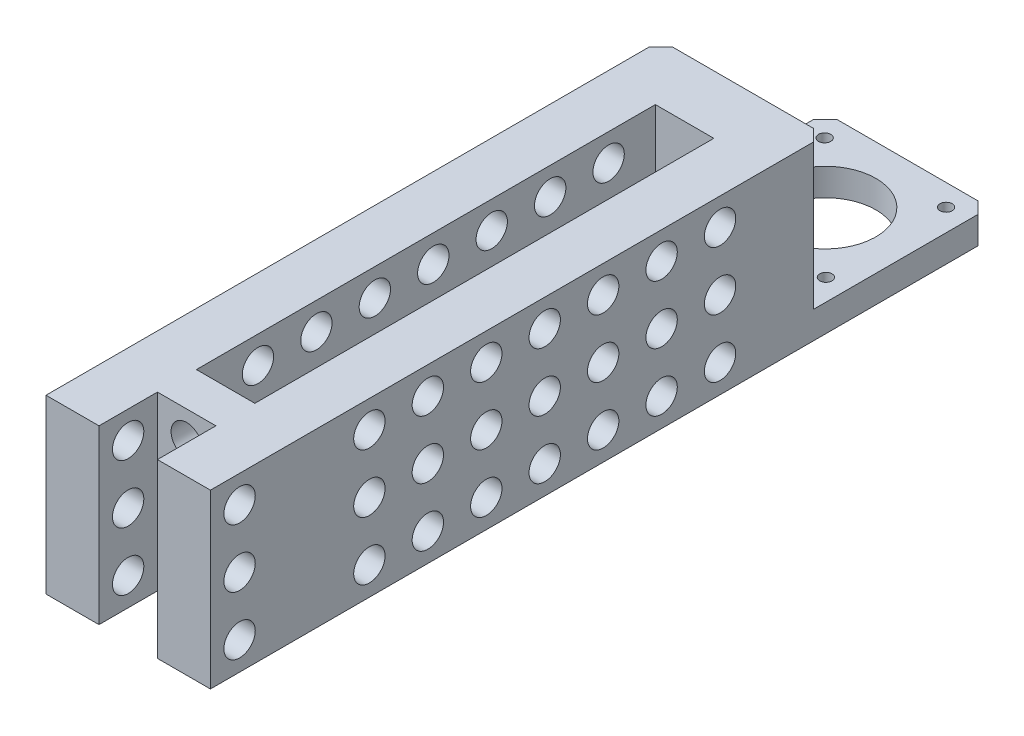
SolidWorks part; units mm, degrees
ref_plane "Front Plane" through (0, 0, 0) normal (0, 0, 1) x (1, 0, 0)
ref_plane "Top Plane" through (0, 0, 0) normal (0, 1, 0) x (1, 0, 0)
ref_plane "Right Plane" through (0, 0, 0) normal (1, 0, 0) x (0, 0, -1)
sketch "Sketch1" plane through (0, 0, 0) normal (0, 1, 0) x (1, 0, 0)
  line L0 (0, 0) -> (-42.2, 0)
  line L1 (-42.2, 0) -> (-42.2, -200)
  line L2 (-42.2, -200) -> (-28.6, -200)
  line L3 (-28.6, -200) -> (-28.6, -185)
  line L4 (-28.6, -185) -> (-13.6, -185)
  line L5 (-13.6, -185) -> (-13.6, -200)
  line L6 (-13.6, -200) -> (0, -200)
  line L7 (0, -200) -> (0, 0)
  line L8 (-28.6, -175) -> (-13.6, -175)
  line L9 (-13.6, -175) -> (-13.6, -57.2)
  line L10 (-13.6, -57.2) -> (-28.6, -57.2)
  line L11 (-28.6, -57.2) -> (-28.6, -175)
  dimension "D1" = 42.2
  dimension "D2" = 57.2
  dimension "D3" = 200
  dimension "D4" = 15
  dimension "D5" = 10
  dimension "D6" = 15
extrude "Boss-Extrude1" add sketch "Sketch1" along normal blind 44.2
sketch "Sketch2" plane through (0, 44.2, 0) normal (0, 1, 0) x (1, 0, 0)
  line L0 (-42.2, 0) -> (0, 0)
  line L1 (0, 0) -> (0, -42.2)
  line L2 (0, -200) -> (0, 0) construction
  line L3 (0, -42.2) -> (-42.2, -42.2)
  line L4 (-42.2, 0) -> (-42.2, -200) construction
  line L5 (-42.2, -42.2) -> (-42.2, 0)
  dimension "D1" = 42.2
extrude "Cut-Extrude1" cut sketch "Sketch2" against normal blind 37.2
sketch "Sketch3" plane through (0, 0, 0) normal (0, -1, 0) x (1, 0, 0)
  line L2 (0, 0) -> (-42.2, 0) construction
  line L3 (-42.2, 0) -> (-42.2, 200) construction
  line L4 (-36.6807, 5.6807) -> (-5.5193, 36.5193) construction
  circle A0 centre (-21.1, 21.1) radius 13
  circle A1 centre (-36.5193, 36.6807) radius 1.575
  circle A2 centre (-5.5193, 36.5193) radius 1.575
  circle A3 centre (-5.6807, 5.5193) radius 1.575
  circle A4 centre (-36.6807, 5.6807) radius 1.575
  circle A5 centre (-21.1, 50) radius 4.1
  circle A6 centre (-5.6, 50) radius 4.1
  circle A7 centre (-36.6, 50) radius 4.1
  point P13 (-21.1, 21.1)
  dimension "D5" = 26
  dimension "D6" = 3.15
  dimension "D8" = 8.2
  dimension "D2" = 21.1
  dimension "D3" = 21.1
  dimension "D4" = 31
  dimension "D7" = 50
  dimension "D9" = 21.1
  dimension "D10" = 2
  dimension "D11" = 2
  dimension "D1" = 4
extrude "Cut-Extrude2" cut sketch "Sketch3" against normal blind 30
sketch "Sketch5" plane through (0, 0, 0) normal (1, 0, 0) x (0, 0, -1)
  line L0 (-200, 44.2) -> (-42.2, 44.2) construction
  line L1 (-42.2, 7) -> (-42.2, 44.2) construction
  line L2 (-200, 44.2) -> (-200, 0) construction
  circle A0 centre (-69.2, 37.2) radius 4.025
  circle A1 centre (-84.2, 37.2) radius 4.025
  circle A2 centre (-99.2, 37.2) radius 4.025
  circle A3 centre (-114.2, 37.2) radius 4.025
  circle A4 centre (-84.2, 22.2) radius 4.025
  circle A5 centre (-99.2, 22.2) radius 4.025
  circle A6 centre (-114.2, 22.2) radius 4.025
  circle A7 centre (-84.2, 7.2) radius 4.025
  circle A8 centre (-99.2, 7.2) radius 4.025
  circle A9 centre (-114.2, 7.2) radius 4.025
  circle A10 centre (-69.2, 22.2) radius 4.025
  circle A11 centre (-69.2, 7.2) radius 4.025
  circle A12 centre (-192.52, 37.2) radius 4.025
  circle A13 centre (-192.52, 22.2) radius 4.025
  circle A14 centre (-192.52, 7.2) radius 4.025
  circle A15 centre (-129.2, 37.2) radius 4.025
  circle A16 centre (-144.2, 37.2) radius 4.025
  circle A17 centre (-159.2, 37.2) radius 4.025
  circle A19 centre (-129.2, 22.2) radius 4.025
  circle A20 centre (-144.2, 22.2) radius 4.025
  circle A21 centre (-159.2, 22.2) radius 4.025
  circle A23 centre (-129.2, 7.2) radius 4.025
  circle A24 centre (-144.2, 7.2) radius 4.025
  circle A25 centre (-159.2, 7.2) radius 4.025
  dimension "D1" = 8.05
  dimension "D6" = 8.05
  dimension "D2" = 7
  dimension "D3" = 27
  dimension "D7" = 7.48
  dimension "D8" = 7
  dimension "D4" = 7
  dimension "D5" = 3
  dimension "D9" = 3
extrude "Cut-Extrude3" cut sketch "Sketch5" against normal blind 55
sketch "Sketch6" plane through (0, 0, 185) normal (0, 0, 1) x (1, 0, 0)
  line L0 (-28.6, 44.2) -> (-13.6, 44.2) construction
  line L1 (0, 44.2) -> (0, 0) construction
  circle A0 centre (-21.1, 37.2) radius 4
  circle A1 centre (-21.1, 22.2) radius 4
  circle A2 centre (-21.1, 7.2) radius 4
  dimension "D1" = 8
  dimension "D2" = 7
  dimension "D3" = 21.1
  dimension "D4" = 3
extrude "Cut-Extrude4" cut sketch "Sketch6" against normal blind 10
chamfer "Chamfer1" distance 3 angle 45 4 edges at (-42.2, 25.6, 42.2) (0, 25.6, 42.2) (0, 3.5, 0) (-42.2, 3.5, 0)
